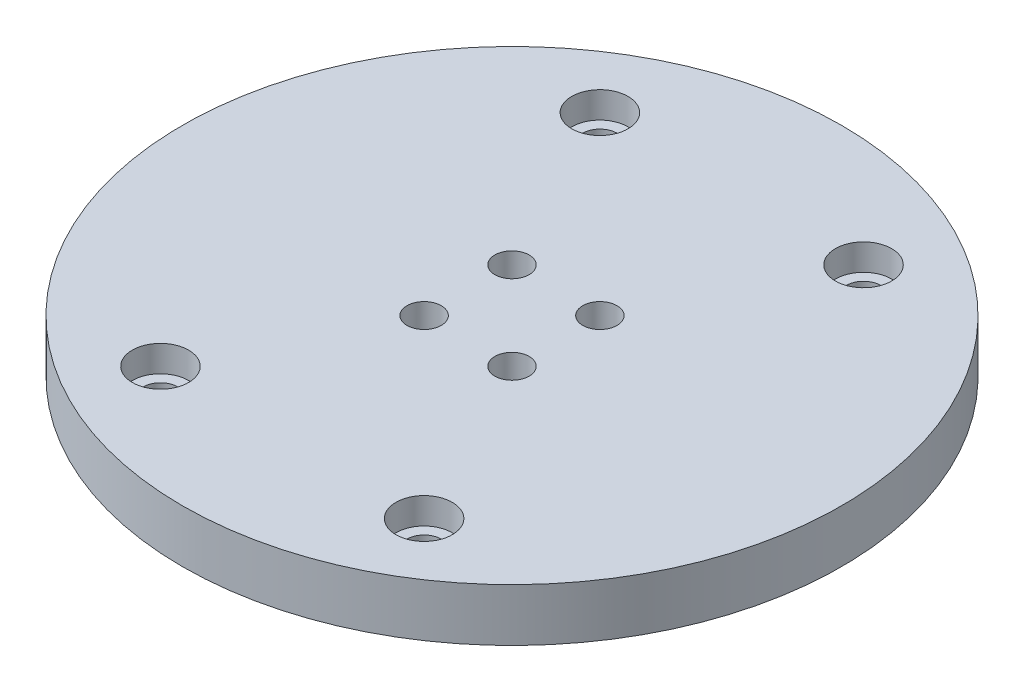
SolidWorks part; units mm, degrees
ref_plane "Ebene vorne" through (0, 0, 0) normal (0, 0, 1) x (1, 0, 0)
ref_plane "Ebene oben" through (0, 0, 0) normal (0, 1, 0) x (1, 0, 0)
ref_plane "Ebene rechts" through (0, 0, 0) normal (1, 0, 0) x (0, 0, -1)
sketch "Skizze1" plane through (0, 0, 0) normal (0, 1, 0) x (1, 0, 0)
  line L1 (0, 0) -> (50, 0) construction
  line L2 (0, 0) -> (0, 60) construction
  line L3 (0, 60) -> (50, 60) construction
  line L4 (50, 0) -> (50, 60) construction
  line L5 (10, 55) -> (40, 55) construction
  line L6 (10, 55) -> (10, 5) construction
  line L7 (10, 5) -> (40, 5) construction
  line L8 (40, 55) -> (40, 5) construction
  circle A5 centre (25, 30) radius 37.5
  point P9 (10, 30)
  point P10 (0, 30)
  point P11 (25, 55)
  point P12 (25, 60)
  point P13 (25, 30)
  dimension "D5" = 75
  dimension "D1" = 50
  dimension "D2" = 60
  dimension "D3" = 10
  dimension "D4" = 5
  dimension "D6" = 15
  dimension "D8" = 25
extrude "Aufsatz-Linear austragen1" add sketch "Skizze1" along normal blind 6
sketch "Skizze2" plane through (0, 0, 0) normal (0, -1, 0) x (1, 0, 0)
  point P0 (20, -25)
  point P1 (30, -25)
  point P2 (30, -35)
  point P3 (25, -30)
  point P4 (20, -35)
  dimension "D1" = 5
  dimension "D2" = 5
  dimension "D3" = 10
  dimension "D4" = 5
hole_wizard "Bohrung3" positions "3D-Skizze4" profile "Skizze6" legacy end condition through all
sketch3d "3D-Skizze4"
  point P0 (20, 0, -25)
  point P3 (30, 0, -25)
  point P6 (30, 0, -35)
  point P9 (20, 0, -35)
sketch "Skizze6" plane through (20, 0, -25) normal (1, 0, 0) x (0, 0, -1)
  line L0 (0, 0) -> (0, 6)
  line L1 (0, 6) -> (1.95, 6)
  line L2 (1.95, 6) -> (1.95, 3)
  line L3 (1.95, 3) -> (3.15, 3)
  line L4 (3.15, 3) -> (3.15, 0)
  line L5 (3.15, 0) -> (0, 0)
  line L6 (0, 110) -> (0, -10) construction
  dimension "Durchmesser" = 3.9
  dimension "Tiefe" = 6
  dimension "Senkdurchmesser1" = 6.3
  dimension "Senktiefe1" = 3
sketch "Skizze7" plane through (0, 6, 0) normal (0, 1, 0) x (1, 0, 0)
  line L1 (10, 55) -> (40, 55) construction
  line L2 (10, 55) -> (10, 5) construction
  line L3 (10, 5) -> (40, 5) construction
  line L4 (40, 55) -> (40, 5) construction
  point P4 (25, 55)
  point P6 (10, 30)
  dimension "D1" = 50
  dimension "D2" = 30
  dimension "D3" = 15
  dimension "D4" = 25
hole_wizard "Bohrung4" positions "3D-Skizze5" profile "Skizze9" legacy end condition through all
sketch3d "3D-Skizze5"
  point P0 (10, 6, -55)
  point P7 (40, 6, -5)
  point P10 (10, 6, -5)
  point P14 (40, 6, -55)
sketch "Skizze9" plane through (10, 6, -55) normal (1, 0, 0) x (0, 0, 1)
  line L0 (0, 0) -> (0, 6)
  line L1 (0, 6) -> (1.95, 6)
  line L2 (1.95, 6) -> (1.95, 3)
  line L3 (1.95, 3) -> (3.2, 3)
  line L4 (3.2, 3) -> (3.2, 0)
  line L5 (3.2, 0) -> (0, 0)
  line L6 (0, 110) -> (0, -10) construction
  dimension "Durchmesser" = 3.9
  dimension "Tiefe" = 6
  dimension "Senkdurchmesser1" = 6.4
  dimension "Senktiefe1" = 3
chamfer "Fase1" [suppressed] distance 0.5 angle 45
chamfer "Fase2" [suppressed] distance 1.2 angle 45
